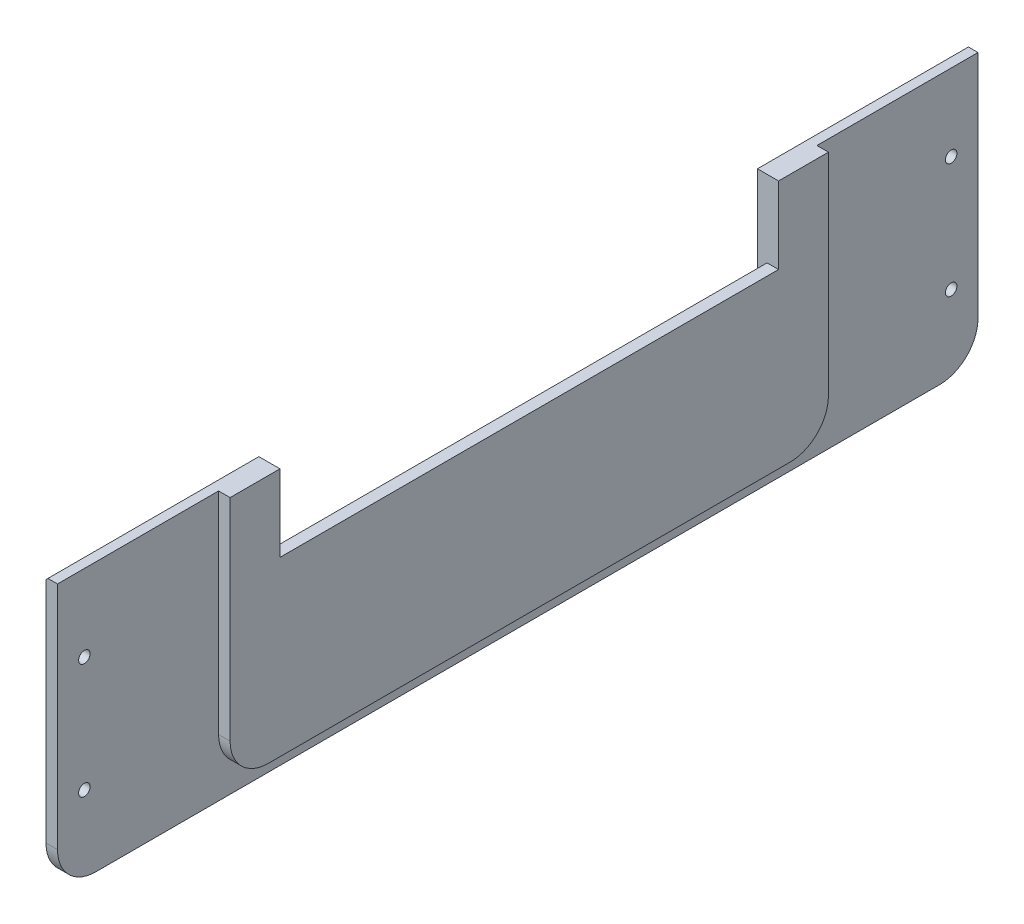
SolidWorks part; units mm, degrees
ref_plane "前视基准面" through (0, 0, 0) normal (0, 0, 1) x (1, 0, 0)
ref_plane "上视基准面" through (0, 0, 0) normal (0, 1, 0) x (1, 0, 0)
ref_plane "右视基准面" through (0, 0, 0) normal (1, 0, 0) x (0, 0, -1)
other "Configuration Table"
sketch "草图1" plane through (0, 0, 0) normal (1, 0, 0) x (0, 0, -1)
  line L1 (-120, 45) -> (120, 45)
  line L2 (-120, 45) -> (-120, -25)
  line L3 (-120, -25) -> (120, -25)
  line L4 (120, 45) -> (120, -25)
  dimension "D1" = 240
  dimension "D2" = 120
  dimension "D3" = 70
  dimension "D4" = 25
extrude "凸台-拉伸1" add sketch "草图1" along normal blind 3
sketch "草图4" plane through (3, 0, 0) normal (1, 0, 0) x (0, 0, -1)
  line L0 (120, 45) -> (-120, 45) construction
  line L1 (-78, 45) -> (78, 45)
  line L2 (-78, 45) -> (-78, -20)
  line L3 (-78, -20) -> (78, -20)
  line L4 (78, 45) -> (78, -20)
  dimension "D1" = 156
  dimension "D2" = 78
  dimension "D3" = 65
extrude "凸台-拉伸3" add sketch "草图4" along normal blind 3
sketch "草图5" plane through (0, 0, 0) normal (-1, 0, 0) x (0, 0, 1)
  line L0 (120, -25) -> (-120, -25) construction
  line L1 (0, 0) -> (0, -50000) construction
  circle A0 centre (113, 25) radius 1.5
  circle A1 centre (113, -5) radius 1.5
  circle A2 centre (-113, -5) radius 1.5
  circle A3 centre (-113, 25) radius 1.5
  dimension "D1" = 30
  dimension "D2" = 3
  dimension "D3" = 113
  dimension "D4" = 20
extrude "切除-拉伸1" cut sketch "草图5" against normal blind 20
fillet "圆角1" radius 10 2 edges at (1.5, -25, 120) (1.5, -25, -120)
fillet "圆角2" radius 10 2 edges at (4.5, -20, 78) (4.5, -20, -78)
sketch "草图7" plane through (0, 0, 0) normal (-1, 0, 0) x (0, 0, 1)
  line L0 (-65, 45) -> (-65, 10)
  line L1 (-120, 45) -> (120, 45) construction
  line L2 (-65, 10) -> (65, 10)
  line L3 (65, 10) -> (65, 45)
  line L4 (65, 45) -> (-65, 45)
  dimension "D1" = 130
  dimension "D2" = 65
  dimension "D3" = 10
extrude "切除-拉伸2" cut sketch "草图7" against normal blind 3
sketch "草图8" plane through (3, 0, 0) normal (-1, 0, 0) x (0, 0, 1)
  line L0 (65, 10) -> (65, 45) construction
  line L1 (-65, 45) -> (65, 45)
  line L2 (-65, 45) -> (-65, 25)
  line L3 (-65, 25) -> (65, 25)
  line L4 (65, 45) -> (65, 25)
  dimension "D1" = 20
extrude "切除-拉伸3" cut sketch "草图8" against normal blind 3
chamfer "倒角1" distance 0.5 angle 45 1 edges at (0, 45, 92.5)
chamfer "倒角2" distance 0.5 angle 45 3 edges at (0, 27.25, 65) (0, 10, 0) (0, 27.25, -65)
